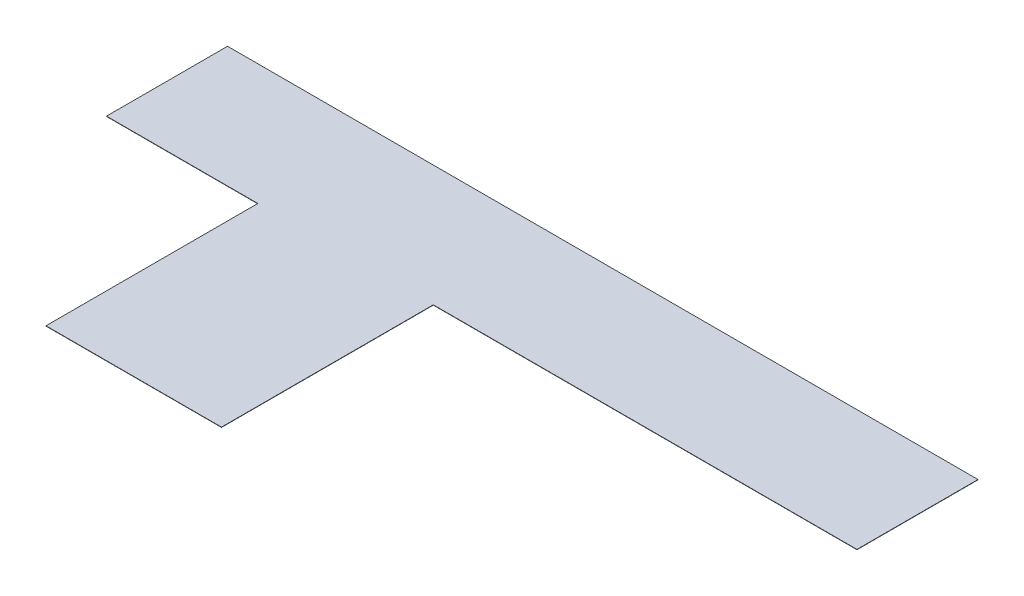
SolidWorks part; units mm, degrees
ref_plane "Front Plane" through (0, 0, 0) normal (0, 0, 1) x (1, 0, 0)
ref_plane "Top Plane" through (0, 0, 0) normal (0, 1, 0) x (1, 0, 0)
ref_plane "Right Plane" through (0, 0, 0) normal (1, 0, 0) x (0, 0, -1)
sketch "Sketch1" plane through (0, 0, 0) normal (0, 1, 0) x (1, 0, 0)
  line L0 (-3700, -1000) -> (-6200, -1000)
  line L1 (6200, -1000) -> (-800, -1000)
  line L2 (6200, -1000) -> (6200, 1000)
  line L3 (6200, 1000) -> (-6200, 1000)
  line L4 (-6200, -1000) -> (-6200, 1000)
  line L5 (6200, -1000) -> (-6200, 1000) construction
  line L6 (6200, 1000) -> (-6200, -1000) construction
  line L8 (-3700, -1000) -> (-3700, -4500)
  line L9 (-3700, -4500) -> (-800, -4500)
  line L10 (-800, -1000) -> (-800, -4500)
  line L11 (-3700, -1000) -> (-800, -4500) construction
  line L12 (-3700, -4500) -> (-800, -1000) construction
  point P0 (0, 0)
  point P10 (-2250, -2750)
  dimension "D1" = 2000
  dimension "D2" = 12400
  dimension "D3" = 7000
  dimension "D4" = 3500
  dimension "D5" = 2900
extrude "Boss-Extrude1" add sketch "Sketch1" along normal blind 5
